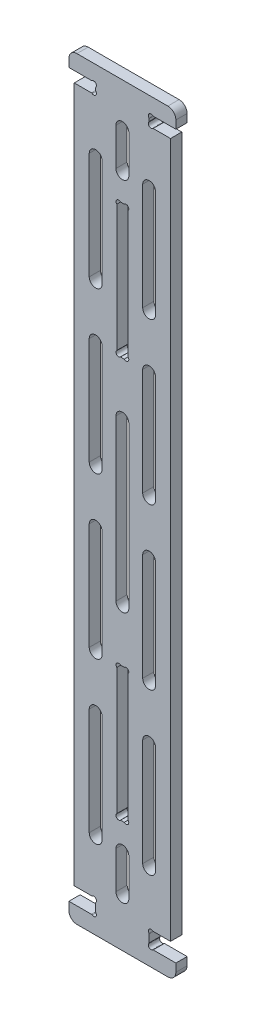
SolidWorks part; units mm, degrees
material "自定义塑料碳纤维-1.6"
ref_plane "前视基准面" through (0, 0, 0) normal (0, 0, 1) x (1, 0, 0)
ref_plane "上视基准面" through (0, 0, 0) normal (0, 1, 0) x (1, 0, 0)
ref_plane "右视基准面" through (0, 0, 0) normal (1, 0, 0) x (0, 0, -1)
other "Configuration Table"
sketch "草图1" plane through (0, 0, 0) normal (0, 0, 1) x (1, 0, 0)
  line L0 (-5, 65) -> (-5, 67)
  line L1 (-9, 65) -> (9, 65)
  line L2 (-9, 65) -> (-9, -65)
  line L3 (-9, -65) -> (9, -65)
  line L4 (9, 65) -> (9, -65)
  line L5 (0, -65) -> (0, 65) construction
  line L6 (-9, 0) -> (9, 0) construction
  line L7 (-5, 67) -> (5, 67)
  line L8 (5, 67) -> (5, 65)
  line L9 (0, 65) -> (0, 67)
  line L10 (-5, -65) -> (-5, -68)
  line L11 (-5, -68) -> (5, -68)
  line L12 (5, -68) -> (5, -65)
  line L13 (0, -65) -> (0, -68)
  point P0 (0, 0)
  dimension "D1" = 130
  dimension "D2" = 18
  dimension "D3" = 10
  dimension "D4" = 2
  dimension "D5" = 10
  dimension "D6" = 3
extrude "凸台-拉伸1" add sketch "草图1" along normal mid plane 2.1 contours L4 L1 L2 L3 | L1 L9 L7 L0 | L9 L1 L8 L7 | L3 L13 L11 L12 | L13 L3 L10 L11
sketch "草图5" plane through (0, 0, 1.05) normal (0, 0, 1) x (1, 0, 0)
  line L0 (5.7071, -65) -> (5, -65.7071) construction
  line L1 (-5, -65.7071) -> (-5.7071, -65) construction
  line L2 (-5, -65) -> (-5, -68) construction
  line L3 (-5.3536, -65.3536) -> (-5, -65)
  line L4 (5.3536, -65.3536) -> (5, -65)
  line L5 (5.7071, 65) -> (5, 65.7071) construction
  line L6 (5, 67) -> (5, 65) construction
  line L7 (5.3536, 65.3536) -> (5, 65)
  line L8 (5, 65) -> (9, 65) construction
  line L9 (-5, 65.7071) -> (-5.7071, 65) construction
  line L10 (-5, 65) -> (-5, 67) construction
  line L11 (-5.3536, 65.3536) -> (-5, 65)
  line L12 (5, -65) -> (9, -65) construction
  circle A0 centre (5.3536, 65.3536) radius 0.5
  circle A1 centre (-5.3536, 65.3536) radius 0.5
  circle A2 centre (5.3536, -65.3536) radius 0.5
  circle A3 centre (-5.3536, -65.3536) radius 0.5
  dimension "D1" = 1
extrude "切除-拉伸3" cut sketch "草图5" against normal through all
sketch "草图2" plane through (0, 0, 1.05) normal (0, 0, 1) x (1, 0, 0)
  line L0 (0, -68) -> (0, 67)
  line L1 (-5, -68) -> (5, -68) construction
  line L2 (-5, 67) -> (5, 67) construction
  line L4 (-1.05, 50.05) -> (1.05, 50.05)
  line L5 (-1.05, 50.05) -> (-1.05, 24.95)
  line L6 (-1.05, 24.95) -> (1.05, 24.95)
  line L7 (1.05, 50.05) -> (1.05, 24.95)
  line L8 (0, 24.95) -> (0, 50.05) construction
  line L9 (-1.05, 37.5) -> (1.05, 37.5) construction
  line L10 (-1.05, -50.05) -> (1.05, -50.05)
  line L11 (-1.05, -50.05) -> (-1.05, -24.95)
  line L12 (-1.05, -24.95) -> (1.05, -24.95)
  line L13 (1.05, -50.05) -> (1.05, -24.95)
  line L14 (0, -24.95) -> (0, -50.05) construction
  line L15 (-1.05, -37.5) -> (1.05, -37.5) construction
  point P6 (0, 37.5)
  point P10 (0, -37.5)
  dimension "D1" = 24.95
  dimension "D2" = 25.1
  dimension "D3" = 2.1
  dimension "D4" = 24.95
  dimension "D5" = 25.1
  dimension "D6" = 2.1
extrude "切除-拉伸1" cut sketch "草图2" against normal blind 10 contours L7 L4 L0 L6 | L5 L6 L0 L4 | L10 L13 L12 L0 | L12 L11 L10 L0
sketch "草图6" plane through (0, 0, 1.05) normal (0, 0, 1) x (1, 0, 0)
  line L0 (0.6964, 25.3036) -> (1.05, 24.95)
  line L1 (-0.6964, 25.3036) -> (-1.05, 24.95)
  line L2 (0.6964, 49.6964) -> (1.05, 50.05)
  line L3 (-0.6964, 49.6964) -> (-1.05, 50.05)
  line L4 (-1.05, 50.05) -> (1.05, 50.05) construction
  line L5 (-1.05, 24.95) -> (1.05, 24.95) construction
  circle A0 centre (0.6964, 49.6964) radius 0.5
  circle A1 centre (-0.6964, 49.6964) radius 0.5
  circle A2 centre (0.6964, 25.3036) radius 0.5
  circle A3 centre (-0.6964, 25.3036) radius 0.5
  dimension "D5" = 1
  dimension "D1" = 45
  dimension "D2" = 45
  dimension "D3" = 45
  dimension "D4" = 45
extrude "切除-拉伸4" cut sketch "草图6" against normal through all
mirror "镜向1" about plane through (0, 0, 0) normal (0, 1, 0) of "切除-拉伸4"
sketch "草图4" plane through (0, 0, 1.05) normal (0, 0, 1) x (1, 0, 0)
  line L1 (5, 65) -> (5, 55) construction
  line L2 (5, 67) -> (5, 65.7071) construction
  line L5 (5.7071, 65) -> (9, 65) construction
  line L6 (5, 55) -> (5, 35)
  line L7 (5, 35) -> (5, 25) construction
  line L8 (5, 25) -> (5, 5)
  line L9 (5, 5) -> (5, -5) construction
  line L10 (5, -5) -> (5, -25)
  line L11 (5, -25) -> (5, -35) construction
  line L12 (5, -35) -> (5, -55)
  line L13 (5, 55) -> (5, 35) construction
  line L15 (6.2, 55) -> (6.2, 35)
  line L16 (3.8, 55) -> (3.8, 35)
  line L17 (5, 25) -> (5, 5) construction
  line L18 (6.2, 25) -> (6.2, 5)
  line L19 (3.8, 25) -> (3.8, 5)
  line L20 (5, -5) -> (5, -25) construction
  line L21 (6.2, -5) -> (6.2, -25)
  line L22 (3.8, -5) -> (3.8, -25)
  line L23 (5, -55) -> (5, -35) construction
  line L24 (3.8, -55) -> (3.8, -35)
  line L25 (6.2, -55) -> (6.2, -35)
  arc A0 (6.2, 55) -> (3.8, 55) centre (5, 55) ccw
  arc A1 (3.8, 35) -> (6.2, 35) centre (5, 35) ccw
  arc A2 (6.2, 25) -> (3.8, 25) centre (5, 25) ccw
  arc A3 (3.8, 5) -> (6.2, 5) centre (5, 5) ccw
  arc A4 (6.2, -5) -> (3.8, -5) centre (5, -5) ccw
  arc A5 (3.8, -25) -> (6.2, -25) centre (5, -25) ccw
  arc A6 (3.8, -55) -> (6.2, -55) centre (5, -55) ccw
  arc A7 (6.2, -35) -> (3.8, -35) centre (5, -35) ccw
  point P0 (5, 45)
  point P18 (5, 15)
  point P23 (5, -15)
  point P28 (5, -45)
  dimension "D9" = 1.2
  dimension "D1" = 10
  dimension "D2" = 20
  dimension "D3" = 10
  dimension "D4" = 20
  dimension "D5" = 10
  dimension "D6" = 20
  dimension "D7" = 10
  dimension "D8" = 20
extrude "切除-拉伸5" cut sketch "草图4" against normal through all
mirror "镜向2" about plane through (0, 0, 0) normal (1, 0, 0) of "切除-拉伸5"
sketch "草图7" plane through (0, 0, 1.05) normal (0, 0, 1) x (1, 0, 0)
  line L0 (0, 62.05) -> (0, 55.05) construction
  line L2 (0, -1.155) -> (0, 1.155) construction
  line L3 (1.2, 62.05) -> (1.2, 55.05)
  line L4 (-1.2, 62.05) -> (-1.2, 55.05)
  line L5 (0, 15) -> (0, -15) construction
  line L6 (1.2, 15) -> (1.2, -15)
  line L7 (-1.2, 15) -> (-1.2, -15)
  line L8 (0, -55.05) -> (0, -62.05) construction
  line L9 (1.2, -55.05) -> (1.2, -62.05)
  line L10 (-1.2, -55.05) -> (-1.2, -62.05)
  line L11 (-0.3429, -50.05) -> (0.3429, -50.05) construction
  line L12 (-0.3429, 50.05) -> (0.3429, 50.05) construction
  arc A0 (1.2, 62.05) -> (-1.2, 62.05) centre (0, 62.05) ccw
  arc A1 (-1.2, 55.05) -> (1.2, 55.05) centre (0, 55.05) ccw
  arc A2 (1.2, 15) -> (-1.2, 15) centre (0, 15) ccw
  arc A3 (-1.2, -15) -> (1.2, -15) centre (0, -15) ccw
  arc A4 (1.2, -55.05) -> (-1.2, -55.05) centre (0, -55.05) ccw
  arc A5 (-1.2, -62.05) -> (1.2, -62.05) centre (0, -62.05) ccw
  point P5 (0, 58.55)
  point P11 (0, 0)
  point P18 (0, -58.55)
  dimension "D6" = 1.2
  dimension "D1" = 5
  dimension "D2" = 5
  dimension "D3" = 7
  dimension "D4" = 7
  dimension "D5" = 30
extrude "切除-拉伸6" cut sketch "草图7" against normal through all
sketch "草图8" plane through (0, 0, 1.05) normal (0, 0, 1) x (1, 0, 0)
  line L0 (5, -68) -> (10, -68)
  line L1 (10, -68) -> (10, -71)
  line L2 (10, -71) -> (-10, -71)
  line L3 (-10, -71) -> (-10, -68)
  line L4 (-10, -68) -> (-5, -68)
  line L5 (5, -68) -> (-5, -68)
  line L6 (5, 67) -> (10, 67)
  line L7 (10, 67) -> (10, 70)
  line L8 (10, 70) -> (-10, 70)
  line L9 (-10, 70) -> (-10, 67)
  line L10 (-10, 67) -> (-5, 67)
  line L11 (-5, 67) -> (5, 67)
  dimension "D1" = 5
  dimension "D2" = 5
  dimension "D3" = 3
  dimension "D4" = 5
  dimension "D5" = 5
  dimension "D6" = 3
extrude "凸台-拉伸2" add sketch "草图8" against normal up to surface (2.1 mm away) up to face at (0, 58.55, -1.05)
sketch "草图9" plane through (0, 0, -1.05) normal (0, 0, -1) x (-1, 0, 0)
  line L0 (-5, -67.2929) -> (-5.7071, -68)
  line L1 (-5, -68) -> (-5, -65.7071) construction
  line L2 (5, -67.2929) -> (5.7071, -68)
  line L3 (5, -65.7071) -> (5, -68) construction
  line L4 (10, -68) -> (5, -68) construction
  line L5 (5.3536, -67.6464) -> (5, -68)
  line L6 (-5, -68) -> (-5.3536, -67.6464)
  line L7 (5, 66.2929) -> (5.7071, 67)
  line L8 (5.3536, 66.6464) -> (5, 67)
  line L9 (-5, 66.2929) -> (-5.7071, 67)
  line L10 (-5.3536, 66.6464) -> (-5, 67)
  line L16 (5.7071, -65) -> (9, -65)
  line L17 (9, -65) -> (9, 65)
  line L18 (9, 65) -> (5.7071, 65)
  line L19 (5, 65.7071) -> (5, 67)
  line L20 (5, 67) -> (10, 67)
  line L21 (-5, 67) -> (-5, 65.7071)
  line L22 (-5.7071, 65) -> (-9, 65)
  line L23 (-9, 65) -> (-9, -65)
  line L24 (-9, -65) -> (-5.7071, -65)
  line L25 (-5, -65.7071) -> (-5, -68)
  line L26 (-5, -68) -> (-10, -68)
  line L27 (-10, -68) -> (-10, -71)
  line L28 (-10, -71) -> (10, -71)
  line L29 (10, -71) -> (10, -68)
  line L30 (10, -68) -> (5, -68)
  line L31 (5, -68) -> (5, -65.7071)
  line L32 (5.7071, -65) -> (9, -65)
  line L33 (9, -65) -> (9, 65)
  line L34 (9, 65) -> (5.7071, 65)
  line L35 (5, 65.7071) -> (5, 67)
  line L37 (-5, 67) -> (-5, 65.7071)
  line L38 (-5.7071, 65) -> (-9, 65)
  line L39 (-9, 65) -> (-9, -65)
  line L40 (-9, -65) -> (-5.7071, -65)
  line L41 (-5, -65.7071) -> (-5, -68)
  line L42 (-5, -68) -> (-10, -68)
  line L43 (-10, -68) -> (-10, -71)
  line L44 (-10, -71) -> (10, -71)
  line L45 (10, -71) -> (10, -68)
  line L46 (10, -68) -> (5, -68)
  line L47 (5, -68) -> (5, -65.7071)
  line L59 (5, 67) -> (10, 67)
  line L60 (10, 67) -> (10, 70)
  line L61 (10, 67) -> (10, 70)
  line L62 (10, 70) -> (-10, 70)
  line L63 (10, 70) -> (-10, 70)
  line L64 (-10, 70) -> (-10, 67)
  line L65 (-10, 70) -> (-10, 67)
  line L66 (-10, 67) -> (-5, 67)
  line L67 (-10, 67) -> (-5, 67)
  circle A0 centre (5.3536, -67.6464) radius 0.5
  circle A1 centre (-5.3536, -67.6464) radius 0.5
  circle A2 centre (5.3536, 66.6464) radius 0.5
  circle A3 centre (-5.3536, 66.6464) radius 0.5
  arc A5 (5.7071, -65) -> (5, -65.7071) centre (5.3536, -65.3536) ccw
  arc A6 (5, 65.7071) -> (5.7071, 65) centre (5.3536, 65.3536) ccw
  arc A7 (-5.7071, 65) -> (-5, 65.7071) centre (-5.3536, 65.3536) ccw
  arc A8 (-5, -65.7071) -> (-5.7071, -65) centre (-5.3536, -65.3536) ccw
  arc A9 (5.7071, -65) -> (5, -65.7071) centre (5.3536, -65.3536) ccw
  arc A10 (5, 65.7071) -> (5.7071, 65) centre (5.3536, 65.3536) ccw
  arc A11 (-5.7071, 65) -> (-5, 65.7071) centre (-5.3536, 65.3536) ccw
  arc A12 (-5, -65.7071) -> (-5.7071, -65) centre (-5.3536, -65.3536) ccw
  dimension "D2" = 1
  dimension "D1" = 0
extrude "切除-拉伸7" cut sketch "草图9" against normal through all contours L41 A1 | L42 A1 | L47 A0 | L46 A0 | L59 A2 | L35 A2 | L37 A3 | L67 A3
fillet "圆角1" radius 0.2 12 edges at (5.7071, 67, 0) (-5.7071, 67, 0) (-5.7071, -68, 0) (5, -67.2929, 0) (5.7071, -68, 0) (-5, -67.2929, 0) (-5.7071, -65, 0) (-5, -65.7071, 0) (5, -65.7071, 0) (5.7071, -65, 0) (5.7071, 65, 0) (-5.7071, 65, 0)
fillet "圆角2" radius 1.5 4 edges at (10, -71, 0) (-10, -71, 0) (10, 70, 0) (-10, 70, 0)
fillet "圆角3" radius 0.2 4 edges at (5, 65.7071, 0) (5, 66.2929, 0) (-5, 66.2929, 0) (-5, 65.7071, 0)
